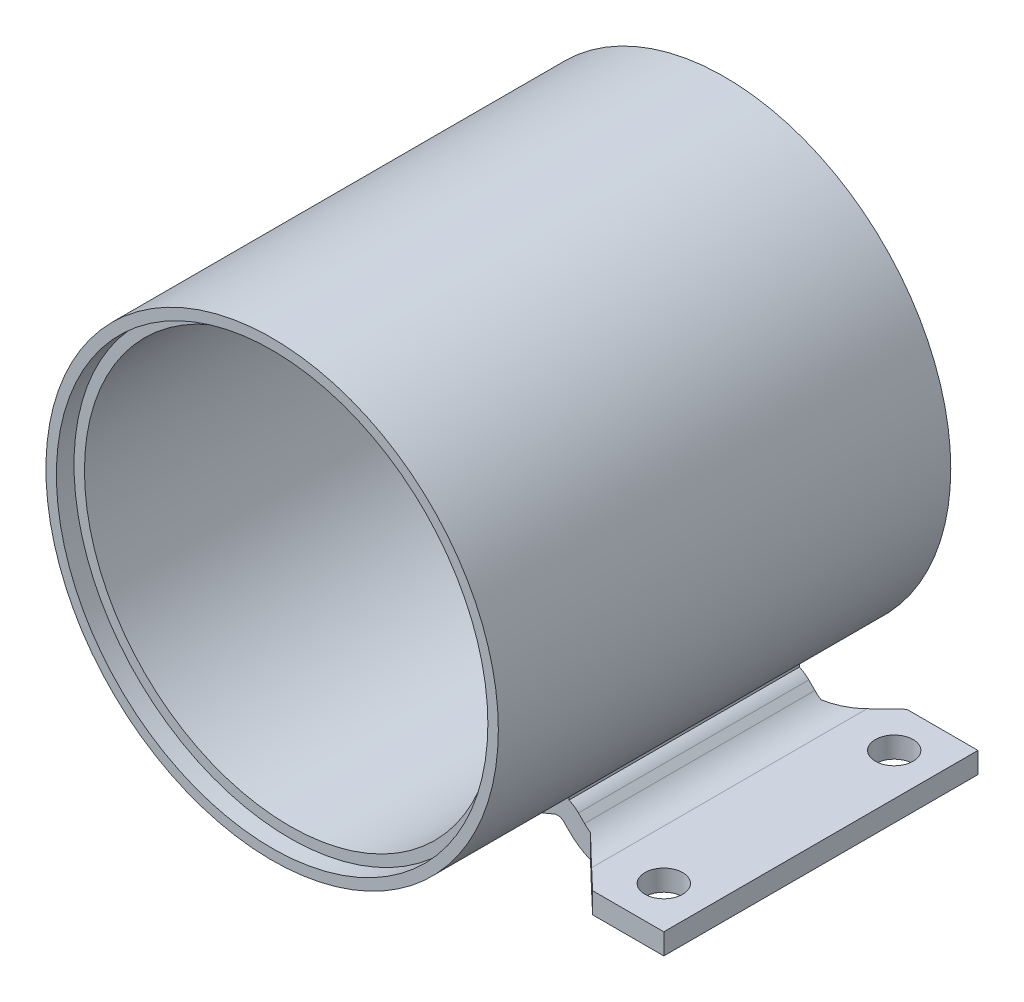
SolidWorks part; units mm, degrees
ref_plane "Plan de face" through (0, 0, 0) normal (0, 0, 1) x (1, 0, 0)
ref_plane "Plan de dessus" through (0, 0, 0) normal (0, 1, 0) x (1, 0, 0)
ref_plane "Plan de droite" through (0, 0, 0) normal (1, 0, 0) x (0, 0, -1)
sketch "Esquisse1" plane through (0, 0, 0) normal (0, 0, 1) x (1, 0, 0)
  circle A0 centre (0, 0) radius 54
  circle A1 centre (0, 0) radius 49
  dimension "D1" = 108
  dimension "D2" = 98
extrude "Extrusion1" add sketch "Esquisse1" along normal blind 108
sketch "Esquisse2" plane through (0, 0, 108) normal (0, 0, 1) x (1, 0, 0)
  circle A0 centre (0, 0) radius 51.5
  dimension "D1" = 103
extrude "Enlèv. mat.-Extru.1" cut sketch "Esquisse2" against normal blind 4.2
sketch "Esquisse3" plane through (0, 0, 0) normal (0, 0, -1) x (-1, 0, 0)
  circle A0 centre (0, 0) radius 51.5
  dimension "D1" = 103
extrude "Enlèv. mat.-Extru.2" cut sketch "Esquisse3" against normal blind 4.2
sketch "Esquisse4" plane through (0, 0, 0) normal (0, 0, -1) x (-1, 0, 0)
  line L0 (0, 0) -> (61.4706, 0) construction
  line L2 (44.6779, 1.5) -> (58.0812, 1.5)
  line L3 (44.6779, 1.5) -> (44.6779, -1.5)
  line L4 (44.6779, -1.5) -> (58.0812, -1.5)
  line L5 (58.0812, 1.5) -> (58.0812, -1.5)
  dimension "D1" = 3
extrude "Enlèv. mat.-Extru.3" cut sketch "Esquisse4" against normal up to surface (4.2 mm away) up to face at (-49, 0, 4.2)
sketch "Esquisse5" plane through (0, 0, 0) normal (0, 0, -1) x (-1, 0, 0)
  line L0 (0, 0) -> (0, -67.556) construction
  line L1 (-60.5, -60) -> (-38.6421, -60)
  line L2 (-60.5, -60) -> (-60.5, -55)
  line L3 (-60.5, -55) -> (-38.6421, -55)
  line L4 (-31.5711, -52.0711) -> (-30.1167, -50.6167)
  line L5 (-28.0355, -55.6066) -> (-26.5811, -54.1522)
  line L6 (28.0355, -55.6066) -> (26.5811, -54.1522)
  line L7 (31.5711, -52.0711) -> (30.1167, -50.6167)
  line L8 (60.5, -55) -> (38.6421, -55)
  line L9 (60.5, -60) -> (60.5, -55)
  line L10 (60.5, -60) -> (38.6421, -60)
  arc A0 (53.9792, 1.5) -> (53.9792, -1.5) centre (0, 0) ccw construction
  arc A1 (-22.2789, -49.1899) -> (22.2789, -49.1899) centre (0, 0) ccw
  arc A2 (-24.3418, -53.7446) -> (24.3418, -53.7446) centre (0, 0) ccw
  arc A3 (-28.0355, -55.6066) -> (-38.6421, -60) centre (-38.6421, -45) cw
  arc A4 (-31.5711, -52.0711) -> (-38.6421, -55) centre (-38.6421, -45) cw
  arc A5 (-26.5811, -54.1522) -> (-24.3418, -53.7446) centre (-25.1669, -55.5664) cw
  arc A6 (-30.1167, -50.6167) -> (-22.2789, -49.1899) centre (-25.1669, -55.5664) cw
  arc A7 (30.1167, -50.6167) -> (22.2789, -49.1899) centre (25.1669, -55.5664) ccw
  arc A8 (26.5811, -54.1522) -> (24.3418, -53.7446) centre (25.1669, -55.5664) ccw
  arc A9 (31.5711, -52.0711) -> (38.6421, -55) centre (38.6421, -45) ccw
  arc A10 (28.0355, -55.6066) -> (38.6421, -60) centre (38.6421, -45) ccw
  point P17 (-34.5, -55)
  dimension "D8" = 15
  dimension "D9" = 10
  dimension "D10" = 2
  dimension "D1" = 60
  dimension "D5" = 121
  dimension "D6" = 26
  dimension "D7" = 45
extrude "Extrusion2" add sketch "Esquisse5" against normal blind 75
sketch "Esquisse6" plane through (0, -60, 0) normal (0, -1, 0) x (1, 0, 0)
  line L0 (43.5, 0) -> (-43.5, 0)
  line L1 (60.5, 0) -> (38.6421, 0) construction
  line L2 (-38.6421, 0) -> (-60.5, 0) construction
  line L3 (0, 0) -> (0, 75) construction
  line L4 (43.5, 0) -> (33, 10)
  line L5 (33, 10) -> (-33, 10)
  line L6 (-33, 10) -> (-43.5, 0)
  line L7 (-60.5, 37.5) -> (60.5, 37.5) construction
  line L8 (-60.5, 75) -> (-60.5, 0) construction
  line L9 (60.5, 75) -> (60.5, 0) construction
  line L10 (-33, 65) -> (-43.5, 75)
  line L11 (33, 65) -> (-33, 65)
  line L12 (43.5, 75) -> (33, 65)
  line L13 (43.5, 75) -> (-43.5, 75)
  line L14 (22.2789, 75) -> (-22.2789, 75) construction
  dimension "D1" = 66
  dimension "D2" = 87
  dimension "D3" = 55
extrude "Enlèv. mat.-Extru.4" cut sketch "Esquisse6" against normal up to surface (28.0039 mm away)
sketch "Esquisse7" plane through (0, 0, 10) normal (0, 0, -1) x (-1, 0, 0)
  line L0 (27.858, -46.2594) -> (27.858, -49.1044)
  line L1 (-27.858, -46.2594) -> (-27.858, -49.1044)
  line L2 (0, 0) -> (0, -64.3893) construction
  arc A0 (53.9792, 1.5) -> (53.9792, -1.5) centre (0, 0) ccw construction
  arc A1 (30.1167, -50.6167) -> (22.2789, -49.1899) centre (25.1669, -55.5664) ccw construction
  arc A2 (22.2789, -49.1899) -> (27.858, -46.2594) centre (0, 0) ccw
  arc A3 (27.858, -49.1044) -> (22.2789, -49.1899) centre (25.1669, -55.5664) ccw
  arc A4 (-27.858, -49.1044) -> (-22.2789, -49.1899) centre (-25.1669, -55.5664) cw
  arc A5 (-22.2789, -49.1899) -> (-27.858, -46.2594) centre (0, 0) cw
extrude "Extrusion3" add sketch "Esquisse7" against normal up to surface (55 mm away) up to face at (0, -53.9097, 65)
sketch "Esquisse8" plane through (0, -60, 0) normal (0, -1, 0) x (1, 0, 0)
  line L0 (0, 0) -> (0, 75.2931) construction
  line L1 (60.5, 37.5) -> (-60.5, 37.5) construction
  line L2 (60.5, 75) -> (60.5, 0) construction
  line L3 (-60.5, 75) -> (-60.5, 0) construction
  circle A0 centre (50.5, 10) radius 4.5
  circle A1 centre (-50.5, 10) radius 4.5
  circle A2 centre (-50.5, 65) radius 4.5
  circle A3 centre (50.5, 65) radius 4.5
  dimension "D1" = 9
  dimension "D2" = 101
  dimension "D3" = 55
  dimension "D4" = 10
extrude "Enlèv. mat.-Extru.5" [suppressed] cut sketch "Esquisse8" against normal blind 5
hole_wizard "Dégagement M81" positions "Esquisse9" profile "Esquisse10" hole size "M8" standard "ISO"
sketch "Esquisse9" plane through (0, -55, 0) normal (0, 1, 0) x (1, 0, 0)
  line L0 (0, 0) -> (0, -77.567) construction
  point P0 (50.5, -10)
  dimension "D1" = 10
  dimension "D2" = 101
sketch "Esquisse10" plane through (50.5, -55, 10) normal (1, 0, 0) x (0, 0, 1)
  line L0 (0, 0) -> (0, 26.7039)
  line L1 (0, 26.7039) -> (4.5, 24)
  line L2 (4.5, 24) -> (4.5, 0)
  line L5 (4.5, 0) -> (0, 0)
  line L10 (0, 26.7039) -> (-4.5, 24) construction
  line L11 (0, -6.35) -> (0, 107.95) construction
  dimension "Diamètre du perçage" = 9
  dimension "Profondeur du perçage" = 24
  dimension "Angle de pointe" = 118
pattern_linear "Répétition linéaire1" count 2 spacing 55 along (0, 0, 1) count 2 spacing 101 along (-1, 0, 0) of "Dégagement M81"
